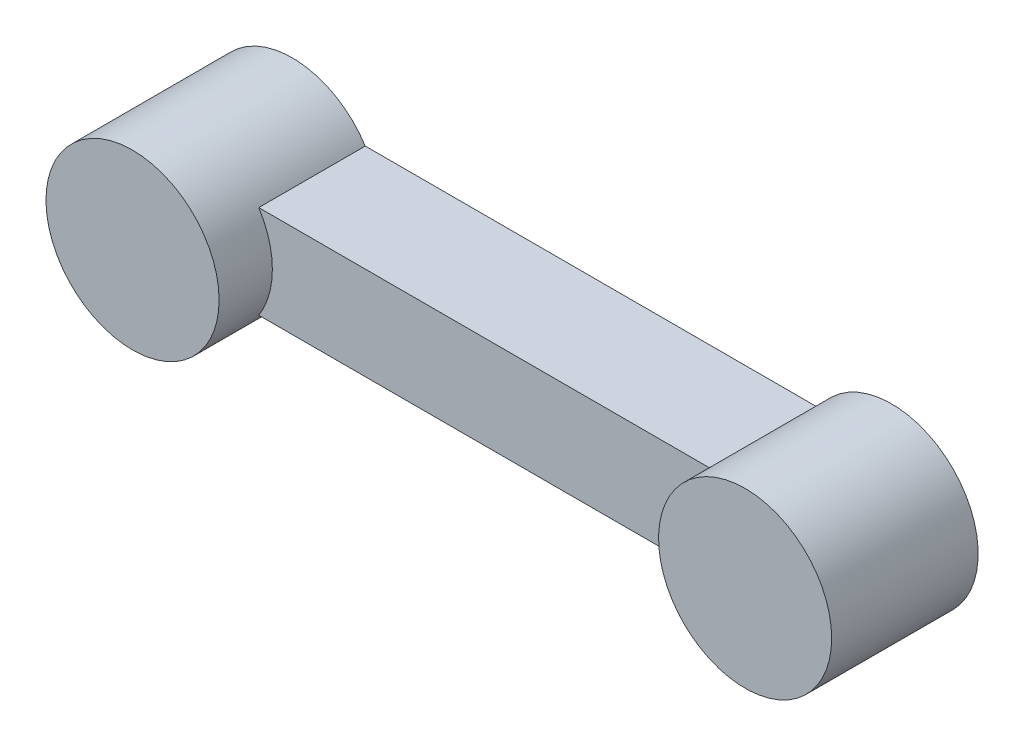
SolidWorks part; units mm, degrees
ref_plane "Front Plane" through (0, 0, 0) normal (0, 0, 1) x (1, 0, 0)
ref_plane "Top Plane" through (0, 0, 0) normal (0, 1, 0) x (1, 0, 0)
ref_plane "Right Plane" through (0, 0, 0) normal (1, 0, 0) x (0, 0, -1)
sketch "草图3" plane through (0, 0, 0) normal (0, 0, 1) x (1, 0, 0)
  line L0 (20, 5) -> (110, 5)
  line L1 (110, 5) -> (110, 19)
  line L2 (110, 19) -> (20, 19)
  line L3 (20, 19) -> (20, 5)
  dimension "x0" = 20
  dimension "x1" = 110
  dimension "y0" = 5
  dimension "y2" = 19
extrude "Bar" add sketch "草图3" along normal blind 16
sketch "草图4" plane through (0, 0, 0) normal (0, 0, 1) x (1, 0, 0)
  circle A0 centre (20, 12) radius 13
  dimension "diameter" = 26
  dimension "x" = 20
  dimension "y" = 12
extrude "RootHub" add sketch "草图4" along normal blind 24
sketch "草图5" plane through (0, 0, 0) normal (0, 0, 1) x (1, 0, 0)
  circle A0 centre (110, 12) radius 13
  dimension "diameter" = 26
  dimension "x" = 110
  dimension "y" = 12
extrude "EndHub" add sketch "草图5" along normal blind 22
